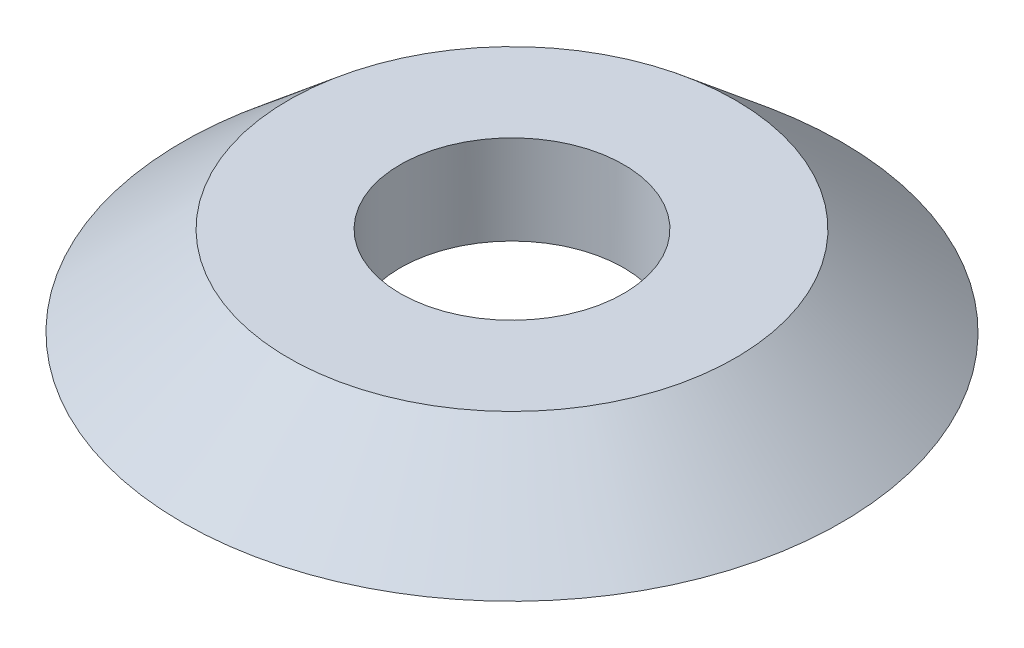
SolidWorks part; units mm, degrees
ref_plane "Front Plane" through (0, 0, 0) normal (0, 0, 1) x (1, 0, 0)
ref_plane "Top Plane" through (0, 0, 0) normal (0, 1, 0) x (1, 0, 0)
ref_plane "Right Plane" through (0, 0, 0) normal (1, 0, 0) x (0, 0, -1)
sketch "Sketch2" plane through (0, 0, 0) normal (0, 0, 1) x (1, 0, 0)
  line L0 (0, 0) -> (-7.375, 0)
  line L1 (0, 0) -> (0, 2)
  line L2 (0, 2) -> (-5, 2)
  line L3 (-5, 2) -> (-7.375, 0)
  dimension "D1" = 7.375
  dimension "D2" = 2
  dimension "D3" = 5
revolve "Revolve4" add sketch "Sketch2" angle 360 about L1
sketch "Sketch3" plane through (0, 2, 0) normal (0, 1, 0) x (1, 0, 0)
  circle A0 centre (0, 0) radius 2.5
  dimension "D1" = 5
extrude "Cut-Extrude1" cut sketch "Sketch3" against normal blind 10
